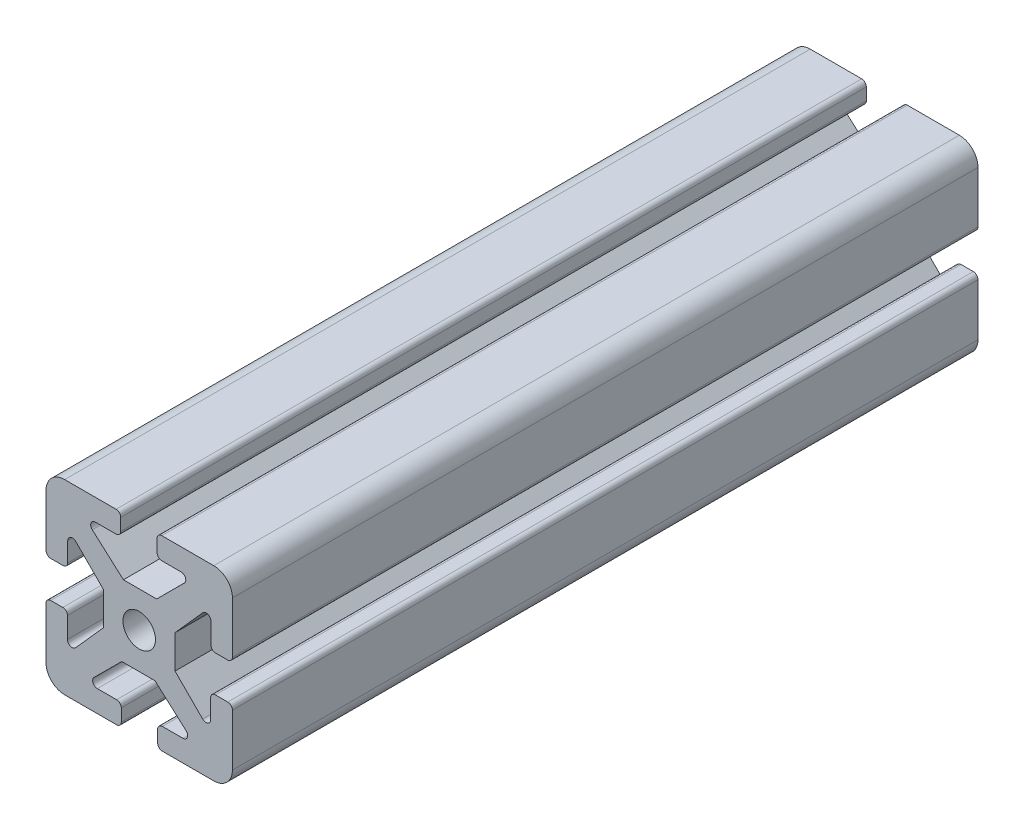
SolidWorks part; units mm, degrees
ref_plane "Front Plane" through (0, 0, 0) normal (0, 0, 1) x (1, 0, 0)
ref_plane "Top Plane" through (0, 0, 0) normal (0, 1, 0) x (1, 0, 0)
ref_plane "Right Plane" through (0, 0, 0) normal (1, 0, 0) x (0, 0, -1)
sketch "Sketch2" plane through (0, 0, 0) normal (0, 0, 1) x (1, 0, 0)
  line L0 (46.607, 139.3199) -> (233.0351, 139.3199) construction
  line L1 (0, 40) -> (40, 0) construction
  line L2 (0, 0) -> (40, 0) construction
  line L3 (0, 0) -> (0, 40) construction
  line L4 (0, 40) -> (40, 40) construction
  line L5 (40, 0) -> (40, 40) construction
  line L6 (0, 0) -> (40, 40) construction
  line L7 (19.4883, 27.6847) -> (23.7499, 27.6847)
  line L8 (23.7499, 27.6847) -> (29.6997, 33.625)
  line L9 (28.9931, 35.3327) -> (24.8456, 35.3327)
  line L10 (23.8456, 36.3327) -> (23.8456, 39)
  line L11 (24.8456, 40) -> (36, 40)
  line L12 (40, 36) -> (40, 24.9611)
  line L13 (39, 23.9611) -> (36.3883, 23.9611)
  line L14 (35.3883, 24.9611) -> (35.3883, 29.4086)
  line L15 (33.6417, 30.0739) -> (27.6847, 23.3888)
  line L16 (27.6847, 23.3888) -> (27.6847, 20.5117)
  line L17 (27.6847, 16.2501) -> (33.625, 10.3003)
  line L18 (30.0739, 6.3583) -> (23.3888, 12.3153)
  line L19 (27.6847, 20.5117) -> (27.6847, 16.2501)
  line L20 (35.3327, 11.0069) -> (35.3327, 15.1544)
  line L21 (36.3327, 16.1544) -> (39, 16.1544)
  line L22 (40, 15.1544) -> (40, 4)
  line L23 (36, 0) -> (24.9611, 0)
  line L24 (23.9611, 1) -> (23.9611, 3.6117)
  line L25 (24.9611, 4.6117) -> (29.4086, 4.6117)
  line L26 (23.3888, 12.3153) -> (20.5117, 12.3153)
  line L27 (16.2501, 12.3153) -> (10.3003, 6.375)
  line L28 (6.3583, 9.9261) -> (12.3153, 16.6112)
  line L29 (20.5117, 12.3153) -> (16.2501, 12.3153)
  line L30 (11.0069, 4.6673) -> (15.1544, 4.6673)
  line L31 (16.1544, 3.6673) -> (16.1544, 1)
  line L32 (15.1544, 0) -> (4, 0)
  line L33 (0, 4) -> (0, 15.0389)
  line L34 (1, 16.0389) -> (3.6117, 16.0389)
  line L35 (4.6117, 15.0389) -> (4.6117, 10.5914)
  line L36 (12.3153, 16.6112) -> (12.3153, 19.4883)
  line L37 (12.3153, 23.7499) -> (6.375, 29.6997)
  line L38 (9.9261, 33.6417) -> (16.6112, 27.6847)
  line L39 (12.3153, 19.4883) -> (12.3153, 23.7499)
  line L40 (4.6673, 28.9931) -> (4.6673, 24.8456)
  line L41 (3.6673, 23.8456) -> (1, 23.8456)
  line L42 (0, 24.8456) -> (0, 36)
  line L43 (4, 40) -> (15.0389, 40)
  line L44 (16.0389, 39) -> (16.0389, 36.3883)
  line L45 (15.0389, 35.3883) -> (10.5914, 35.3883)
  line L46 (16.6112, 27.6847) -> (19.4883, 27.6847)
  circle A1 centre (20, 20) radius 3.4925
  arc A2 (40, 24.9611) -> (39, 23.9611) centre (39, 24.9611) cw
  arc A3 (36.3883, 23.9611) -> (35.3883, 24.9611) centre (36.3883, 24.9611) cw
  arc A4 (24.8456, 35.3327) -> (23.8456, 36.3327) centre (24.8456, 36.3327) cw
  arc A5 (23.8456, 39) -> (24.8456, 40) centre (24.8456, 39) cw
  arc A6 (29.6997, 33.625) -> (28.9931, 35.3327) centre (28.9931, 34.3327) ccw
  arc A7 (35.3883, 29.4086) -> (33.6417, 30.0739) centre (34.3883, 29.4086) ccw
  arc A8 (40, 36) -> (36, 40) centre (36, 36) ccw
  arc A9 (35.3327, 15.1544) -> (36.3327, 16.1544) centre (36.3327, 15.1544) cw
  arc A10 (39, 16.1544) -> (40, 15.1544) centre (39, 15.1544) cw
  arc A11 (36, 0) -> (40, 4) centre (36, 4) ccw
  arc A12 (24.9611, 0) -> (23.9611, 1) centre (24.9611, 1) cw
  arc A13 (23.9611, 3.6117) -> (24.9611, 4.6117) centre (24.9611, 3.6117) cw
  arc A14 (29.4086, 4.6117) -> (30.0739, 6.3583) centre (29.4086, 5.6117) ccw
  arc A15 (33.625, 10.3003) -> (35.3327, 11.0069) centre (34.3327, 11.0069) ccw
  arc A16 (15.1544, 4.6673) -> (16.1544, 3.6673) centre (15.1544, 3.6673) cw
  arc A17 (16.1544, 1) -> (15.1544, 0) centre (15.1544, 1) cw
  arc A18 (0, 4) -> (4, 0) centre (4, 4) ccw
  arc A19 (0, 15.0389) -> (1, 16.0389) centre (1, 15.0389) cw
  arc A20 (3.6117, 16.0389) -> (4.6117, 15.0389) centre (3.6117, 15.0389) cw
  arc A21 (4.6117, 10.5914) -> (6.3583, 9.9261) centre (5.6117, 10.5914) ccw
  arc A22 (10.3003, 6.375) -> (11.0069, 4.6673) centre (11.0069, 5.6673) ccw
  arc A23 (4.6673, 24.8456) -> (3.6673, 23.8456) centre (3.6673, 24.8456) cw
  arc A24 (1, 23.8456) -> (0, 24.8456) centre (1, 24.8456) cw
  arc A25 (4, 40) -> (0, 36) centre (4, 36) ccw
  arc A26 (15.0389, 40) -> (16.0389, 39) centre (15.0389, 39) cw
  arc A27 (16.0389, 36.3883) -> (15.0389, 35.3883) centre (15.0389, 36.3883) cw
  arc A28 (10.5914, 35.3883) -> (9.9261, 33.6417) centre (10.5914, 34.3883) ccw
  arc A29 (6.375, 29.6997) -> (4.6673, 28.9931) centre (5.6673, 28.9931) ccw
  point P24 (40, 23.9611)
  point P31 (23.8456, 40)
  dimension "D1" = 40
  dimension "D3" = 1
  dimension "D4" = 4
  dimension "D2" = 40
  dimension "D5" = 4
extrude "Boss-Extrude1" add sketch "Sketch2" along normal blind 160
